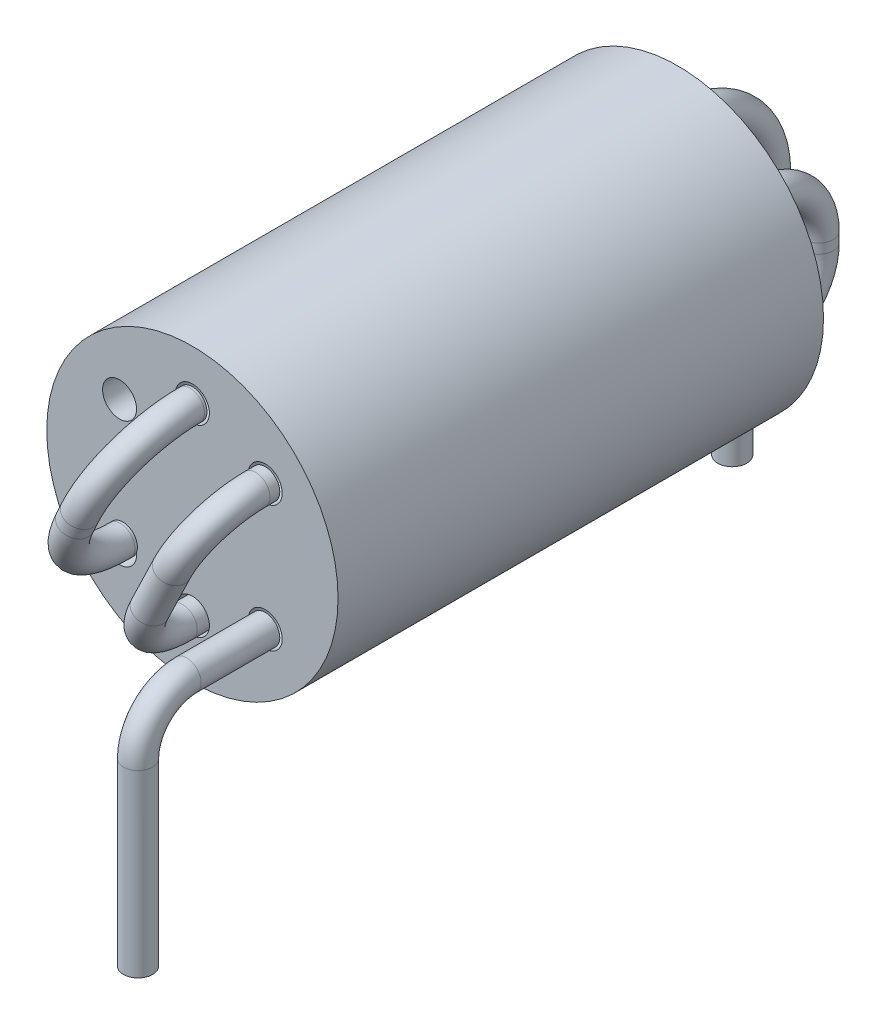
SolidWorks part; units mm, degrees
material "Fonte grise (SN)"
ref_plane "Plan de face" through (0, 0, 0) normal (0, 0, 1) x (1, 0, 0)
ref_plane "Plan de dessus" through (0, 0, 0) normal (0, 1, 0) x (1, 0, 0)
ref_plane "Plan de droite" through (0, 0, 0) normal (1, 0, 0) x (0, 0, -1)
sketch "Esquisse1" plane through (0, 0, 0) normal (0, 0, 1) x (1, 0, 0)
  circle A0 centre (0, 0) radius 3
  dimension "D1" = 6
extrude "Boss.-Extru.1" add sketch "Esquisse1" along normal blind 10
sketch "Esquisse2" plane through (0, 0, 10) normal (0, 0, 1) x (1, 0, 0)
  circle A0 centre (-1.5, -1.3) radius 0.35
  circle A1 centre (0, -1.8097) radius 0.35
  circle A2 centre (0, 1.9769) radius 0.35
  circle A3 centre (-1.5, 1.3) radius 0.35
  circle A4 centre (1.5, 1.3) radius 0.35
  circle A5 centre (1.5, -1.3) radius 0.35
  dimension "D1" = 0.7
  dimension "D2" = 0.7
  dimension "D3" = 0.7
  dimension "D4" = 0.7
  dimension "D5" = 0.7
  dimension "D10" = 0.7
  dimension "D6" = 1.5
  dimension "D7" = 1.5
  dimension "D8" = 1.3
  dimension "D9" = 1.3
  dimension "D11" = 1.5
ref_plane "Plan1" through (-0.7482, 0.3425, 0) normal (-0.9093, 0.4162, 0) x (0, 0, 1)
ref_plane "Plan2" through (0.7082, -0.3416, 0) normal (-0.9007, 0.4345, 0) x (0, 0, 1)
sketch "Esquisse3" plane through (-0.7482, 0.3425, 0) normal (-0.9093, 0.4162, 0) x (0, 0, 1)
  line L0 (10, 1.7975) -> (10.05, 1.7975)
  line L1 (11.65, 0.1975) -> (11.65, -0.0455)
  line L2 (10.05, -1.6455) -> (10, -1.6455)
  line L3 (10, -1.9955) -> (10, -1.2955) construction
  line L4 (10, -3) -> (10, 3) construction
  arc A0 (10.05, -1.6455) -> (11.65, -0.0455) centre (10.05, -0.0455) ccw
  arc A1 (11.65, 0.1975) -> (10.05, 1.7975) centre (10.05, 0.1975) ccw
  dimension "D1" = 1.6
  dimension "D2" = 1.65
extrude "Enlèv. mat.-Extru.1" cut sketch "Esquisse2" against normal through all
sketch "Esquisse4" plane through (0, 0, 10) normal (0, 0, 1) x (1, 0, 0)
  circle A0 centre (-1.433, -1.1537) radius 0.3
  dimension "D1" = 0.6
sweep "Balayage3" add profiles "Esquisse4" path "Esquisse3"
ref_plane "Plan4" through (0.002, -0.0009, 0) normal (-0.9093, 0.4162, 0) x (0, 0, 1)
sketch "Esquisse5" plane through (0, 0, 10) normal (0, 0, 1) x (1, 0, 0)
  circle A0 centre (1.5, -1.3) radius 0.3
  dimension "D1" = 0.6
sketch "Esquisse6" plane through (0, 0, 0) normal (1, 0, 0) x (0, 0, -1)
  line L0 (-10, -1.3) -> (-11.62, -1.3)
  line L1 (-10, -1) -> (-10, -1.6) construction
  line L2 (-12.62, -2.3) -> (-12.62, -6)
  line L3 (-10, -3) -> (0, -3) construction
  arc A0 (-12.62, -2.3) -> (-11.62, -1.3) centre (-11.62, -2.3) cw
  point P9 (-12.62, -1.3)
  dimension "D3" = 1
  dimension "D1" = 2.62
  dimension "D2" = 3
sweep "Balayage4" add profiles "Esquisse5" path "Esquisse6"
sketch "Esquisse7" plane through (0, 0, 0) normal (0, 0, -1) x (-1, 0, 0)
  circle A0 centre (0, 1.9769) radius 0.3
  dimension "D1" = 0.6
sketch "Esquisse8" plane through (0, 0, 0) normal (1, 0, 0) x (0, 0, -1)
  line L0 (0, 1.9769) -> (0.1, 1.9769)
  line L1 (0, 1.6769) -> (0, 2.2769) construction
  line L2 (1.9, 0.1769) -> (1.9, -0.0097)
  line L3 (0, -1.8097) -> (0.1, -1.8097)
  arc A0 (1.9, -0.0097) -> (0.1, -1.8097) centre (0.1, -0.0097) cw
  arc A1 (1.9, 0.1769) -> (0.1, 1.9769) centre (0.1, 0.1769) ccw
  point P12 (1.9, 1.9769)
  dimension "D2" = 1.8
  dimension "D1" = 1.9
sweep "Balayage6" add profiles "Esquisse7" path "Esquisse8"
sketch "Esquisse9" plane through (0, 0, 0) normal (0, 0, -1) x (-1, 0, 0)
  circle A0 centre (1.5, -1.3) radius 0.3
  dimension "D1" = 0.6
ref_plane "Plan5" through (-1.5, 0, 0) normal (1, 0, 0) x (0, 0, -1)
sketch "Esquisse11" plane through (-1.5, 0, 0) normal (1, 0, 0) x (0, 0, -1)
  line L0 (1.62, -1.3) -> (0, -1.3)
  line L1 (0, -1.6) -> (0, -1) construction
  line L2 (2.62, -2.3) -> (2.62, -6)
  line L3 (-12.92, -6) -> (-12.32, -6) construction
  arc A0 (2.62, -2.3) -> (1.62, -1.3) centre (1.62, -2.3) ccw
  point P9 (2.62, -1.3)
  dimension "D2" = 1
  dimension "D1" = 2.62
sweep "Balayage7" add profiles "Esquisse9" path "Esquisse11"
sketch "Esquisse12" plane through (0, 0, 0) normal (0, 0, -1) x (-1, 0, 0)
  circle A0 centre (-1.5, 1.3) radius 0.3
  dimension "D1" = 0.6
ref_plane "Plan6" through (1.5, 0, 0) normal (1, 0, 0) x (0, 0, -1)
sketch "Esquisse13" plane through (1.5, 0, 0) normal (1, 0, 0) x (0, 0, -1)
  line L0 (0, 1.3) -> (0.2, 1.3)
  line L1 (1.4, 0.1) -> (1.4, -0.1)
  line L2 (0, -1.3) -> (0.2, -1.3)
  line L3 (0, -1) -> (0, -1.6) construction
  arc A0 (1.4, 0.1) -> (0.2, 1.3) centre (0.2, 0.1) ccw
  arc A1 (0.2, -1.3) -> (1.4, -0.1) centre (0.2, -0.1) ccw
  point P7 (1.4, 1.3)
  dimension "D2" = 1.2
  dimension "D3" = 1.2
  dimension "D1" = 1.4
sweep "Balayage8" add profiles "Esquisse12" path "Esquisse13"
sketch "Esquisse14" plane through (0, 0, 10) normal (0, 0, 1) x (1, 0, 0)
  circle A0 centre (1.5, 1.3) radius 0.3
  dimension "D1" = 0.6
sketch "Esquisse16" plane through (0.7082, -0.3416, 0) normal (-0.9007, 0.4345, 0) x (0, 0, 1)
  line L0 (10, 1.8226) -> (10.2, 1.8226)
  line L1 (10, 1.5226) -> (10, 2.1226) construction
  line L2 (11.4, 0.6226) -> (11.4, -0.4299)
  line L3 (10.2, -1.6299) -> (9.8041, -1.6299)
  arc A0 (11.4, -0.4299) -> (10.2, -1.6299) centre (10.2, -0.4299) cw
  arc A1 (11.4, 0.6226) -> (10.2, 1.8226) centre (10.2, 0.6226) ccw
  dimension "D1" = 1.2
  dimension "D2" = 1.4
sweep "Balayage9" add profiles "Esquisse14" path "Esquisse16"
